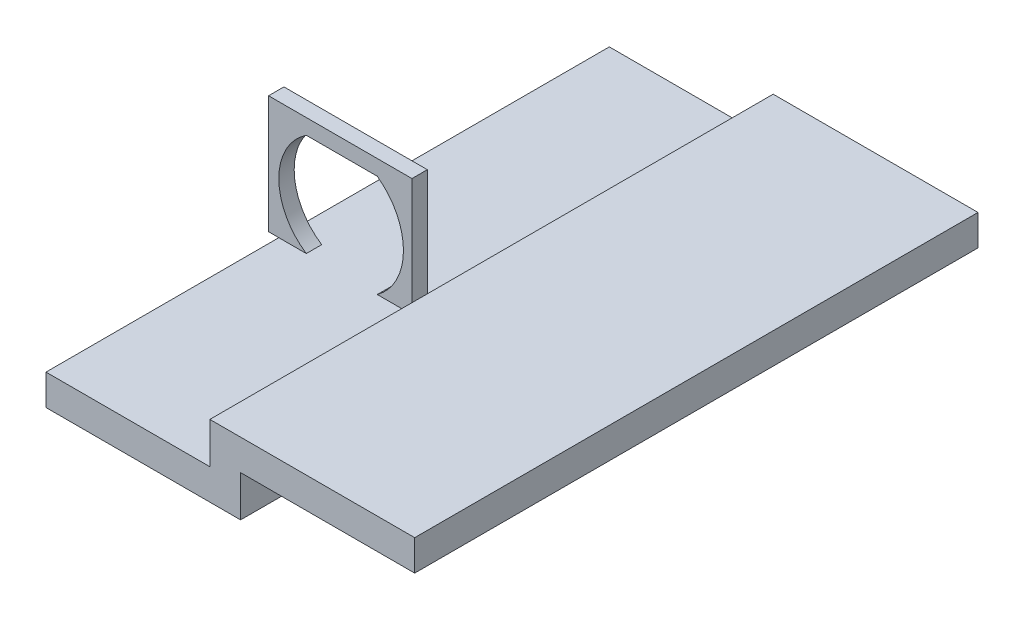
SolidWorks part; units mm, degrees
ref_plane "Ebene vorne" through (0, 0, 0) normal (0, 0, 1) x (1, 0, 0)
ref_plane "Ebene oben" through (0, 0, 0) normal (0, 1, 0) x (1, 0, 0)
ref_plane "Ebene rechts" through (0, 0, 0) normal (1, 0, 0) x (0, 0, -1)
sketch "Skizze1" plane through (0, 0, 0) normal (0, 0, 1) x (1, 0, 0)
  line L0 (-19, 0) -> (0, 0)
  line L1 (0, 4) -> (17, 4)
  line L2 (17, 4) -> (17, 7)
  line L3 (17, 7) -> (-3, 7)
  line L4 (-3, 7) -> (-3, 3)
  line L5 (-3, 3) -> (-19, 3)
  line L6 (-19, 3) -> (-19, 0)
  line L7 (0, 0) -> (0, 4)
  point P7 (-19, 1.5)
  point P10 (-3, 5)
  point P11 (-9.5, 0)
  dimension "D1" = 16
  dimension "D2" = 20
  dimension "D3" = 3
  dimension "D4" = 3
  dimension "D5" = 3
  dimension "D6" = 7
extrude "Aufsatz-Linear austragen1" add sketch "Skizze1" along normal blind 55 contours L0 L7 L1 L2 L3 L4 L5 L6
sketch "Skizze4" plane through (0, 3, 0) normal (0, 1, 0) x (1, 0, 0)
  line L1 (-20, -30.768) -> (-20, -32.268)
  line L2 (-20, -32.268) -> (-6, -32.268)
  line L3 (-6, -32.268) -> (-6, -30.768)
  line L4 (-6, -30.768) -> (-20, -30.768)
  line L5 (-19, -55) -> (-19, 0) construction
  line L6 (-7, -45.69) -> (-7, -30.89) construction
  point P4 (-20, -31.518)
  dimension "D1" = 1.5
  dimension "D2" = 14
  dimension "D3" = 1
  dimension "D4" = 1
extrude "Aufsatz-Linear austragen2" add sketch "Skizze4" along normal blind 11.5
sketch "Skizze7" plane through (0, 0, 32.268) normal (0, 0, 1) x (1, 0, 0)
  line L0 (-9.387, 3) -> (-16.3166, 3)
  line L1 (-3, 3) -> (-19, 3) construction
  line L2 (-7.3, 13) -> (-18.7, 13) construction
  line L3 (-9.387, 13) -> (-16.3166, 13)
  arc A0 (-9.387, 3) -> (-9.387, 13) centre (-13, 8) ccw
  arc A1 (-16.3166, 13) -> (-16.3166, 3) centre (-13, 8) ccw
  point P1 (0, 0)
  point P9 (-16.3809, 3)
  point P14 (0, 0)
  point P15 (0, 0)
  point P16 (-16.3312, 3.0097)
extrude "Schnitt-Linear austragen1" cut sketch "Skizze7" against normal blind 11.5
